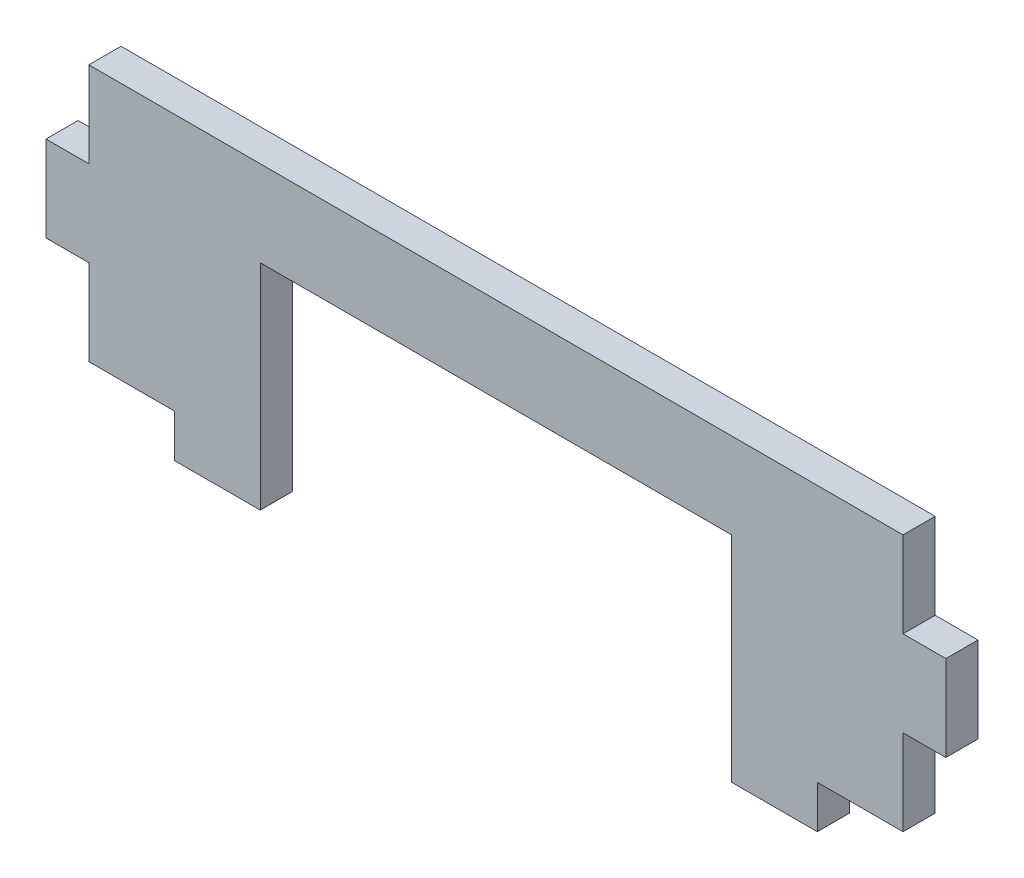
SolidWorks part; units mm, degrees
ref_plane "前视" through (0, 0, 0) normal (0, 0, 1) x (1, 0, 0)
ref_plane "上视" through (0, 0, 0) normal (0, 1, 0) x (1, 0, 0)
ref_plane "右视" through (0, 0, 0) normal (1, 0, 0) x (0, 0, -1)
sketch "草图1" plane through (0, 0, 0) normal (0, 0, 1) x (1, 0, 0)
  line L0 (0, 31.4086) -> (0, -61.4645) construction
  line L1 (-38, 0) -> (38, 0)
  line L2 (-38, 0) -> (-38, -8)
  line L3 (-38, -8) -> (-42, -8)
  line L4 (-42, -8) -> (-42, -16)
  line L5 (-42, -16) -> (-38, -16)
  line L6 (-38, -24) -> (-30, -24)
  line L7 (-30, -24) -> (-30, -28)
  line L8 (-30, -28) -> (-22, -28)
  line L9 (-22, -28) -> (-22, -24)
  line L10 (-22, -16) -> (-22, -8)
  line L11 (-38, -16) -> (-38, -24)
  line L12 (22, -8) -> (-22, -8)
  line L16 (38, -16) -> (38, -24)
  line L17 (22, -28) -> (22, -24)
  line L18 (30, -28) -> (22, -28)
  line L19 (30, -24) -> (30, -28)
  line L20 (38, -24) -> (30, -24)
  line L21 (42, -16) -> (38, -16)
  line L22 (42, -8) -> (42, -16)
  line L23 (38, -8) -> (42, -8)
  line L24 (38, 0) -> (38, -8)
  line L25 (-22, -24) -> (-22, -16)
  line L26 (22, -24) -> (22, -16)
  line L28 (22, -16) -> (22, -8)
  point P19 (0, -16)
  point P20 (0, -8)
  point P21 (0, -24)
  point P22 (0, 0)
  dimension "D1" = 22
  dimension "D2" = 8
  dimension "D3" = 38
  dimension "D4" = 8
  dimension "D5" = 8
  dimension "D6" = 4
  dimension "D7" = 4
  dimension "D8" = 4
  dimension "D9" = 4
  dimension "D10" = 8
  dimension "D12" = 8
extrude "凸台-拉伸1" add sketch "草图1" along normal blind 3
